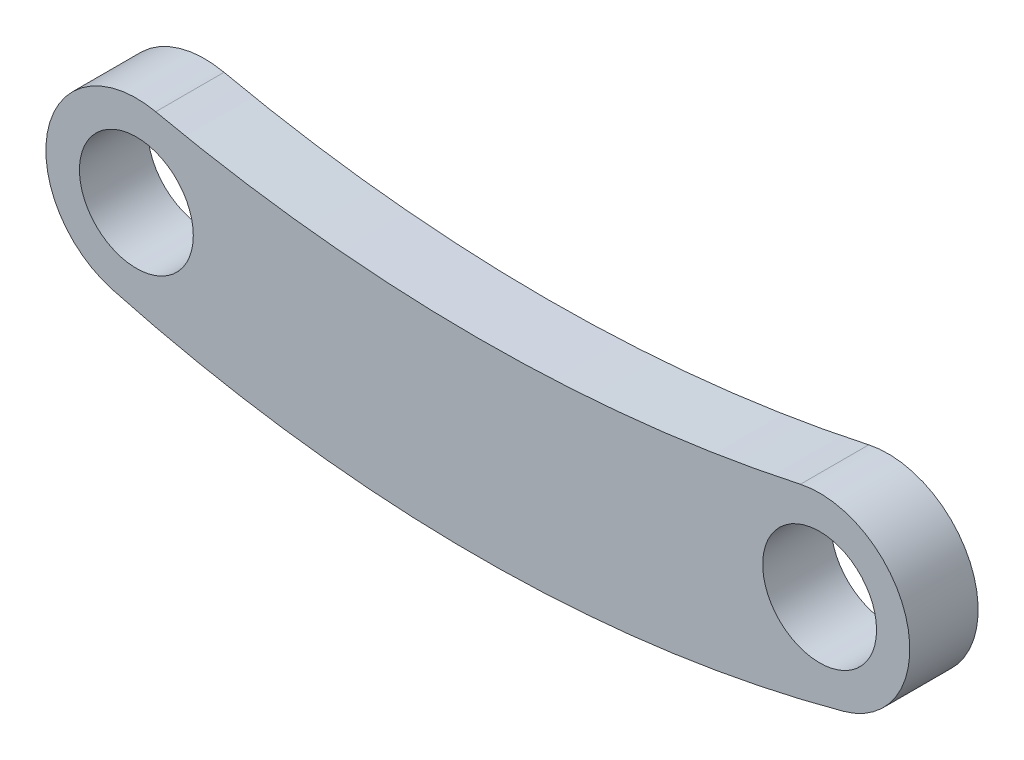
SolidWorks part; units mm, degrees
ref_plane "Front Plane" through (0, 0, 0) normal (0, 0, 1) x (1, 0, 0)
ref_plane "Top Plane" through (0, 0, 0) normal (0, 1, 0) x (1, 0, 0)
ref_plane "Right Plane" through (0, 0, 0) normal (1, 0, 0) x (0, 0, -1)
sketch "Sketch1" plane through (0, 0, 0) normal (0, 0, 1) x (1, 0, 0)
  line L0 (-15, 0) -> (15, 0) construction
  line L1 (-15, 0) -> (15, 0) construction
  circle A0 centre (-15, 0) radius 2.5
  circle A1 centre (15, 0) radius 2.5
  arc A2 (-14.1508, 3.8818) -> (-16.0367, -3.836) centre (-15, 0) ccw
  arc A3 (16.0365, -3.8224) -> (14.1569, 3.8697) centre (15, 0) ccw
  arc A4 (-14.1508, 3.8818) -> (14.1569, 3.8697) centre (0.0308, 68.7043) ccw
  arc A5 (-16.0367, -3.836) -> (16.0365, -3.8224) centre (-0.0251, 55.4111) ccw
  point P4 (0, 0)
  point P7 (0, 0)
  dimension "D2" = 5
  dimension "D3" = 5
  dimension "D6" = 66.3556
  dimension "D7" = 61.3725
  dimension "D1" = 30
  dimension "D4" = 7.6921
  dimension "D5" = 7.7178
extrude "Boss-Extrude1" add sketch "Sketch1" along normal blind 3
